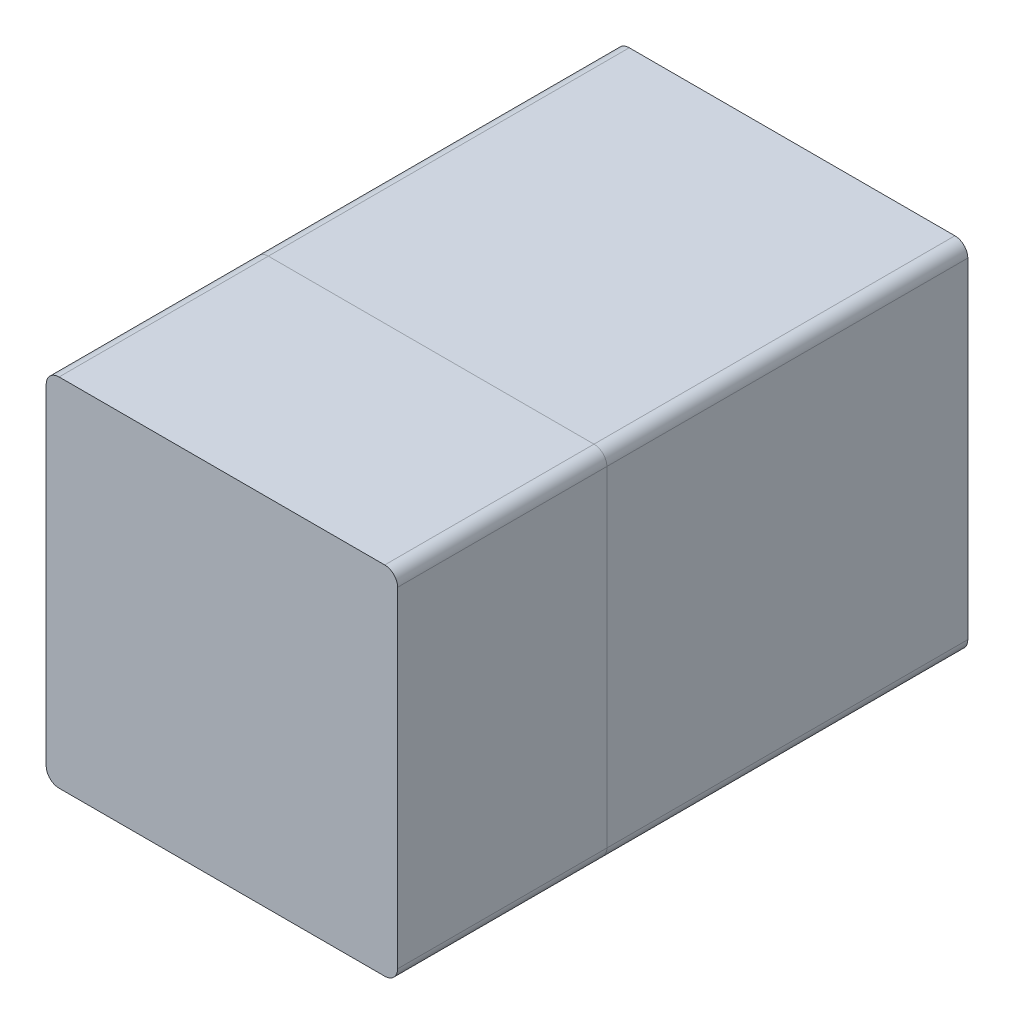
SolidWorks part; units mm, degrees
material "Custom Plastic"
ref_plane "X-Y Datum" through (0, 0, 0) normal (0, 0, 1) x (1, 0, 0)
ref_plane "X-Z Datum" through (0, 0, 0) normal (0, 1, 0) x (1, 0, 0)
ref_plane "Y-Z Datum" through (0, 0, 0) normal (1, 0, 0) x (0, 0, -1)
sketch "Sketch1" plane through (0, 0, 0) normal (0, 0, 1) x (1, 0, 0)
  line L0 (-36.8935, 36.449) -> (-36.8935, -36.449)
  line L1 (-36.5125, 36.068) -> (36.5125, 36.068) construction
  line L2 (-36.5125, 36.068) -> (-36.5125, -36.068) construction
  line L3 (-36.5125, -36.068) -> (36.5125, -36.068) construction
  line L4 (36.5125, 36.068) -> (36.5125, -36.068) construction
  line L5 (-36.5125, 36.068) -> (36.5125, -36.068) construction
  line L6 (-36.5125, -36.068) -> (36.5125, 36.068) construction
  line L7 (-36.8935, -36.449) -> (36.8935, -36.449)
  line L8 (36.8935, 36.449) -> (36.8935, -36.449)
  line L9 (-36.8935, 36.449) -> (36.8935, 36.449)
  point P0 (0, 0)
  dimension "D1" = 73.025
  dimension "D2" = 72.136
  dimension "D3" = 0.381
extrude "Boss-Extrude1" add sketch "Sketch1" along normal blind 123.698
shell "Shell1" thickness 4
sketch "Sketch2" plane through (0, 0, 123.698) normal (0, 0, 1) x (1, 0, 0)
  line L1 (36.8935, 36.449) -> (-36.8935, 36.449) construction
  line L2 (-36.8935, 36.449) -> (-36.8935, -36.449) construction
  line L3 (-36.8935, -36.449) -> (36.8935, -36.449) construction
  line L4 (40.8935, 40.449) -> (-40.8935, 40.449)
  line L5 (-40.8935, 40.449) -> (-40.8935, -40.449)
  line L6 (-40.8935, -40.449) -> (40.8935, -40.449)
  line L7 (40.8935, -40.449) -> (40.8935, 40.449)
  line L8 (40.8935, 40.449) -> (-40.8935, 40.449)
  line L9 (-40.8935, 40.449) -> (-40.8935, -40.449)
  line L10 (-40.8935, -40.449) -> (40.8935, -40.449)
  line L11 (40.8935, -40.449) -> (40.8935, 40.449)
  line L12 (36.8935, -36.449) -> (36.8935, 36.449) construction
  line L13 (36.8935, 36.449) -> (-36.8935, 36.449)
  line L14 (-36.8935, 36.449) -> (-36.8935, -36.449)
  line L15 (-36.8935, -36.449) -> (36.8935, -36.449)
  line L16 (36.8935, -36.449) -> (36.8935, 36.449)
  dimension "D1" = 0
extrude "Boss-Extrude2" add sketch "Sketch2" along normal blind 1
sketch "Sketch7" plane through (0, 0, 124.698) normal (0, 0, 1) x (1, 0, 0)
  line L4 (40.8935, -40.449) -> (40.8935, 40.449)
  line L5 (40.8935, 40.449) -> (-40.8935, 40.449)
  line L6 (-40.8935, 40.449) -> (-40.8935, -40.449)
  line L7 (-40.8935, -40.449) -> (40.8935, -40.449)
  line L8 (40.8935, -40.449) -> (40.8935, 40.449)
  line L9 (40.8935, 40.449) -> (-40.8935, 40.449)
  line L10 (-40.8935, 40.449) -> (-40.8935, -40.449)
  line L11 (-40.8935, -40.449) -> (40.8935, -40.449)
  dimension "D1" = 0
extrude "Boss-Extrude5" add sketch "Sketch7" along normal blind 4
sketch "Sketch3" plane through (0, -40.449, 0) normal (0, -1, 0) x (1, 0, 0)
  line L4 (-40.8935, -4) -> (40.8935, -4)
  line L5 (40.8935, -4) -> (40.8935, 128.698)
  line L6 (40.8935, 128.698) -> (-40.8935, 128.698)
  line L7 (-40.8935, 128.698) -> (-40.8935, -4)
  line L8 (-40.8935, -4) -> (40.8935, -4)
  line L9 (40.8935, -4) -> (40.8935, 128.698)
  line L11 (-40.8935, 128.698) -> (-40.8935, -4)
  line L12 (40.8935, 128.698) -> (-40.8935, 128.698)
  dimension "D1" = 0
extrude "Boss-Extrude3" add sketch "Sketch3" along normal blind 2
sketch "Sketch4" plane through (0, -42.449, 0) normal (0, -1, 0) x (1, 0, 0)
  circle A0 centre (-22.225, 109.648) radius 3.025
  circle A1 centre (22.225, 109.648) radius 3.025
  circle A2 centre (-22.225, 15.05) radius 3.025
  circle A3 centre (22.225, 15.05) radius 3.025
  dimension "D1" = 6.05
extrude "Cut-Extrude2" cut sketch "Sketch4" against normal blind 5
fillet "Fillet1" radius 3 4 edges at (-40.8935, 40.449, 62.349) (-40.8935, -42.449, 62.349) (40.8935, 40.449, 62.349) (40.8935, -42.449, 62.349)
ref_plane "Plane1" through (0, 0, 80) normal (0, 0, 1) x (1, 0, 0)
split "Split1" trim tools "Plane1" bodies to split 104 resulting bodies 105 106
sketch "Sketch5" plane through (0, 0, 80) normal (0, 0, 1) x (1, 0, 0)
  line L0 (-38.8935, 38.449) -> (-38.8935, -38.449)
  line L1 (-38.8935, -38.449) -> (38.8935, -38.449)
  line L2 (38.8935, -38.449) -> (38.8935, 38.449)
  line L3 (38.8935, 38.449) -> (-38.8935, 38.449)
  line L4 (36.8935, 36.449) -> (-36.8935, 36.449)
  line L5 (-36.8935, 36.449) -> (-36.8935, -36.449)
  line L6 (-36.8935, -36.449) -> (36.8935, -36.449)
  line L7 (36.8935, -36.449) -> (36.8935, 36.449)
  line L8 (36.8935, 36.449) -> (-36.8935, 36.449)
  line L9 (-36.8935, 36.449) -> (-36.8935, -36.449)
  line L10 (-36.8935, -36.449) -> (36.8935, -36.449)
  line L11 (36.8935, -36.449) -> (36.8935, 36.449)
  dimension "D1" = 0
  dimension "D2" = 2
extrude "Boss-Extrude4" add sketch "Sketch5" along normal blind 20
sketch "Sketch6" plane through (0, 0, 80) normal (0, 0, -1) x (-1, 0, 0)
  line L4 (-38.8935, 38.449) -> (-38.8935, -38.449) construction
  line L5 (-38.8935, -38.449) -> (38.8935, -38.449) construction
  line L6 (38.8935, -38.449) -> (38.8935, 38.449) construction
  line L7 (38.8935, 38.449) -> (-38.8935, 38.449) construction
  line L16 (36.8935, 36.449) -> (-36.8935, 36.449)
  line L17 (-36.8935, 36.449) -> (-36.8935, -36.449)
  line L18 (-36.8935, -36.449) -> (36.8935, -36.449)
  line L19 (36.8935, -36.449) -> (36.8935, 36.449)
  line L20 (36.8935, 36.449) -> (-36.8935, 36.449) construction
  line L21 (-36.8935, 36.449) -> (-36.8935, -36.449) construction
  line L22 (-36.8935, -36.449) -> (36.8935, -36.449) construction
  line L23 (36.8935, -36.449) -> (36.8935, 36.449) construction
  line L24 (-39.0435, 38.599) -> (-39.0435, -38.599)
  line L25 (-39.0435, -38.599) -> (39.0435, -38.599)
  line L26 (39.0435, -38.599) -> (39.0435, 38.599)
  line L27 (39.0435, 38.599) -> (-39.0435, 38.599)
  dimension "D1" = 0
  dimension "D2" = 2
  dimension "D3" = 0.15
extrude "Cut-Extrude3" cut sketch "Sketch6" against normal blind 21
